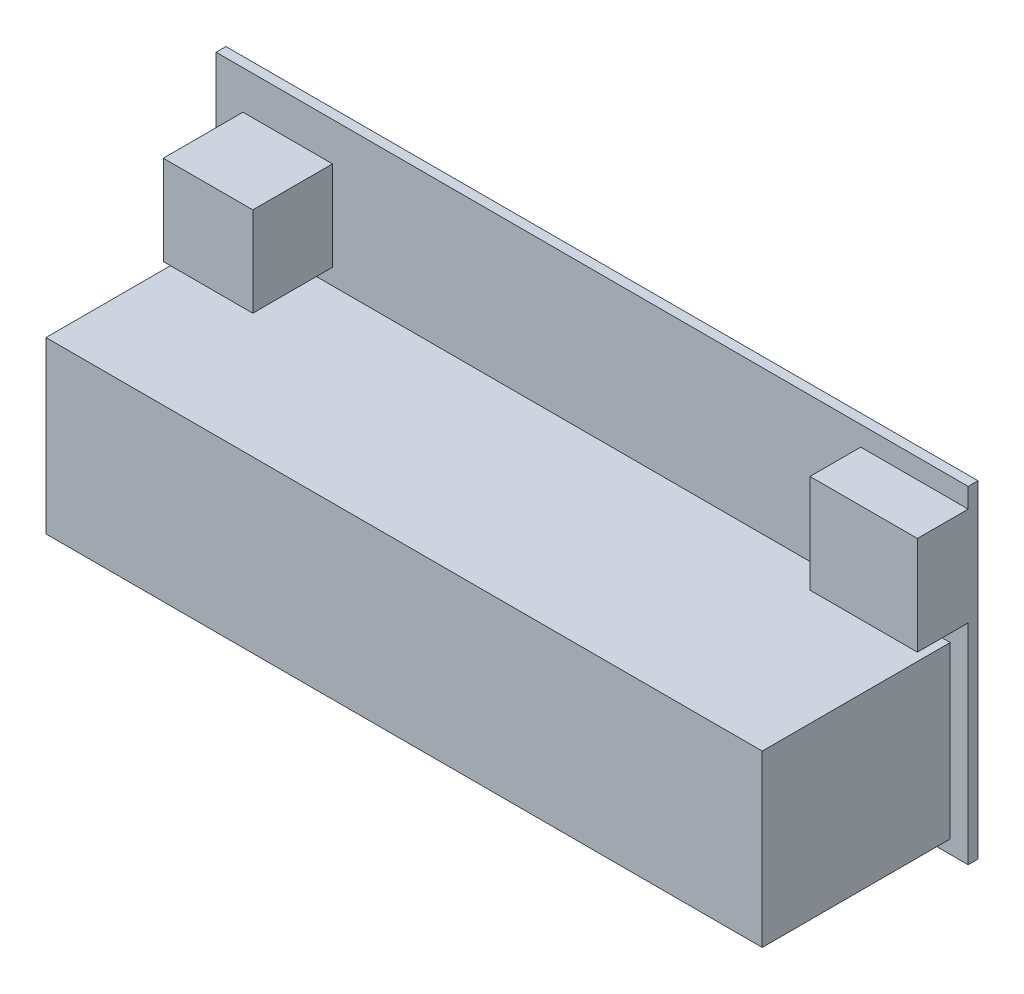
SolidWorks part; units mm, degrees
ref_plane "前基準面" through (0, 0, 0) normal (0, 0, 1) x (1, 0, 0)
ref_plane "上基準面" through (0, 0, 0) normal (0, 1, 0) x (1, 0, 0)
ref_plane "右基準面" through (0, 0, 0) normal (1, 0, 0) x (0, 0, -1)
sketch "草圖1" plane through (0, 0, 0) normal (0, 0, 1) x (1, 0, 0)
  line L1 (-27.6819, 10.3958) -> (56.3181, 10.3958)
  line L2 (-27.6819, 10.3958) -> (-27.6819, -26.2042)
  line L3 (-27.6819, -26.2042) -> (56.3181, -26.2042)
  line L4 (56.3181, 10.3958) -> (56.3181, -26.2042)
  dimension "D1" = 36.6
  dimension "D2" = 84
extrude "填料-伸長1" add sketch "草圖1" along normal blind 1.1
sketch "草圖2" plane through (0, 0, 1.1) normal (0, 0, 1) x (1, 0, 0)
  line L0 (56.3181, 10.3958) -> (-27.6819, 10.3958) construction
  line L1 (-24.6819, 6.0958) -> (-14.6819, 6.0958)
  line L2 (-24.6819, 6.0958) -> (-24.6819, -3.9042)
  line L3 (-24.6819, -3.9042) -> (-14.6819, -3.9042)
  line L4 (-14.6819, 6.0958) -> (-14.6819, -3.9042)
  line L5 (-27.6819, 10.3958) -> (-27.6819, -26.2042) construction
  dimension "D1" = 4.3
  dimension "D2" = 3
  dimension "D3" = 10
  dimension "D4" = 10
extrude "填料-伸長2" add sketch "草圖2" along normal blind 8.9
sketch "草圖3" plane through (0, 0, 1.1) normal (0, 0, 1) x (1, 0, 0)
  line L0 (56.3181, -26.2042) -> (56.3181, 10.3958) construction
  line L1 (44.3181, 8.1958) -> (56.3181, 8.1958)
  line L2 (44.3181, 8.1958) -> (44.3181, -2.8042)
  line L3 (44.3181, -2.8042) -> (56.3181, -2.8042)
  line L4 (56.3181, 8.1958) -> (56.3181, -2.8042)
  line L5 (56.3181, 10.3958) -> (-27.6819, 10.3958) construction
  dimension "D1" = 2.2
  dimension "D2" = 12
  dimension "D3" = 11
extrude "填料-伸長3" add sketch "草圖3" along normal blind 5.67
sketch "草圖4" plane through (0, 0, 1.1) normal (0, 0, 1) x (1, 0, 0)
  line L0 (-27.6819, 10.3958) -> (-27.6819, -26.2042) construction
  line L1 (-25.6819, -5.7042) -> (54.3181, -5.7042)
  line L2 (-25.6819, -5.7042) -> (-25.6819, -24.7042)
  line L3 (-25.6819, -24.7042) -> (54.3181, -24.7042)
  line L4 (54.3181, -5.7042) -> (54.3181, -24.7042)
  line L5 (-27.6819, -26.2042) -> (56.3181, -26.2042) construction
  line L6 (56.3181, -26.2042) -> (56.3181, -2.8042) construction
  dimension "D1" = 2
  dimension "D2" = 1.5
  dimension "D3" = 2
  dimension "D4" = 19
extrude "填料-伸長4" add sketch "草圖4" along normal blind 21
